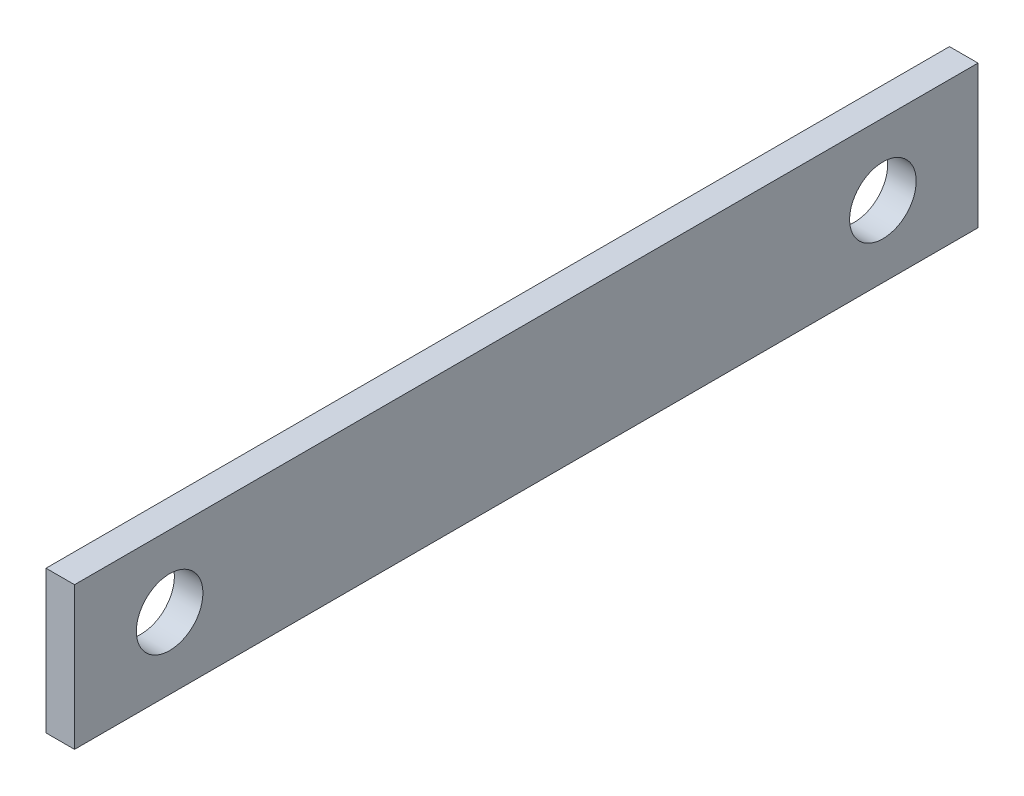
SolidWorks part; units mm, degrees
material "ASTM A36 Steel"
ref_plane "Front Plane" through (0, 0, 0) normal (0, 0, 1) x (1, 0, 0)
ref_plane "Top Plane" through (0, 0, 0) normal (0, 1, 0) x (1, 0, 0)
ref_plane "Right Plane" through (0, 0, 0) normal (1, 0, 0) x (0, 0, -1)
sketch "Sketch1" plane through (0, 0, 0) normal (1, 0, 0) x (0, 0, -1)
  line L1 (-95, -15) -> (95, -15)
  line L2 (-95, -15) -> (-95, 15)
  line L3 (-95, 15) -> (95, 15)
  line L4 (95, -15) -> (95, 15)
  line L5 (-95, -15) -> (95, 15) construction
  line L6 (-95, 15) -> (95, -15) construction
  circle A0 centre (-75, 0) radius 7
  circle A1 centre (75, 0) radius 7
  point P0 (0, 0)
  dimension "D3" = 14
  dimension "D4" = 14
  dimension "D5" = 20
  dimension "D6" = 20
  dimension "D1" = 30
  dimension "D2" = 190
extrude "Boss-Extrude1" add sketch "Sketch1" along normal blind 6
